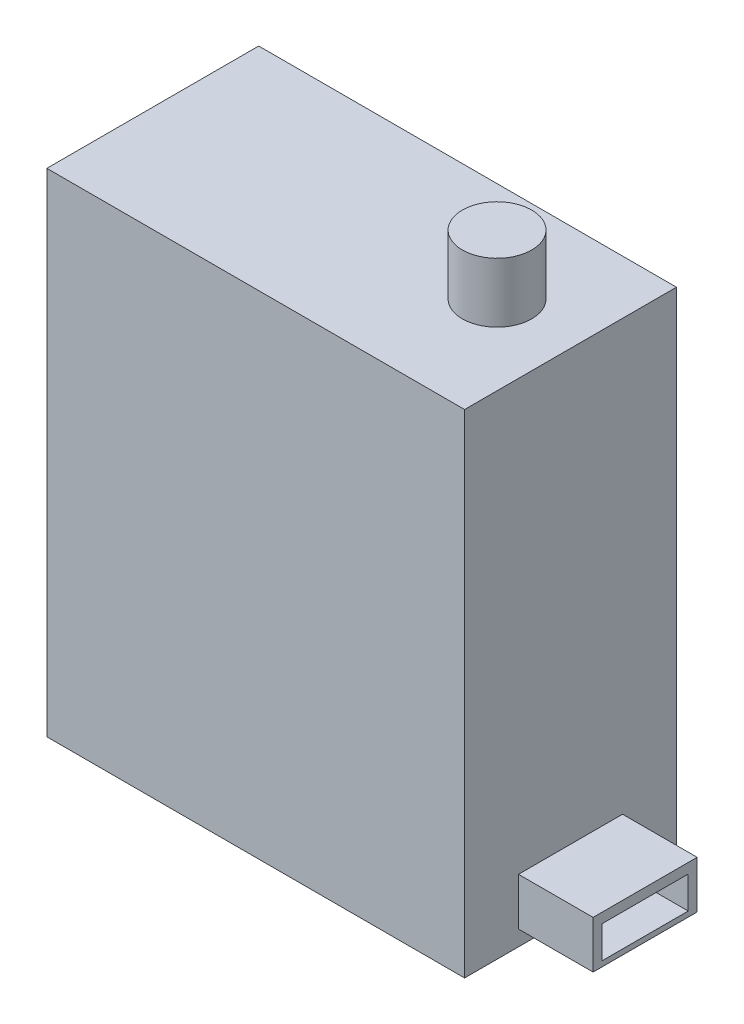
SolidWorks part; units mm, degrees
ref_plane "Front Plane" through (0, 0, 0) normal (0, 0, 1) x (1, 0, 0)
ref_plane "Top Plane" through (0, 0, 0) normal (0, 1, 0) x (1, 0, 0)
ref_plane "Right Plane" through (0, 0, 0) normal (1, 0, 0) x (0, 0, -1)
sketch "Sketch1" plane through (0, 0, 0) normal (0, 1, 0) x (1, 0, 0)
  line L1 (0, 0) -> (-28, 0)
  line L2 (0, 0) -> (0, 14.2)
  line L3 (0, 14.2) -> (-28, 14.2)
  line L4 (-28, 0) -> (-28, 14.2)
  dimension "D1" = 28
  dimension "D2" = 14.2
extrude "Boss-Extrude1" add sketch "Sketch1" along normal blind 33
sketch "Sketch2" plane through (0, 33, 0) normal (0, 1, 0) x (1, 0, 0)
  circle A0 centre (-5.3315, 7.5063) radius 2.3219
  dimension "D1" = 4.6438
extrude "Boss-Extrude3" add sketch "Sketch2" along normal blind 4
sketch "Sketch3" plane through (0, 0, 0) normal (1, 0, 0) x (0, 0, -1)
  line L1 (10.5874, 1.0363) -> (3.6126, 1.0363)
  line L2 (10.5874, 1.0363) -> (10.5874, 4.2126)
  line L3 (10.5874, 4.2126) -> (3.6126, 4.2126)
  line L4 (3.6126, 1.0363) -> (3.6126, 4.2126)
  line L5 (10.5874, 1.0363) -> (3.6126, 4.2126) construction
  line L6 (10.5874, 4.2126) -> (3.6126, 1.0363) construction
  point P0 (7.1, 2.6245)
  dimension "D1" = 24.485
  dimension "D2" = 6.9748
  dimension "D3" = 3.1763
  dimension "D4" = 6.9748
extrude "Boss-Extrude4" add sketch "Sketch3" along normal blind 5
sketch "Sketch4" plane through (5, 0, 0) normal (1, 0, 0) x (0, 0, -1)
  line L5 (4.2112, 1.393) -> (9.9888, 1.393)
  line L6 (4.2112, 1.393) -> (4.2112, 3.5428)
  line L7 (4.2112, 3.5428) -> (9.9888, 3.5428)
  line L8 (9.9888, 1.393) -> (9.9888, 3.5428)
  line L9 (4.2112, 1.393) -> (9.9888, 3.5428) construction
  line L10 (4.2112, 3.5428) -> (9.9888, 1.393) construction
  point P0 (7.1, 2.4679)
extrude "Cut-Extrude1" cut sketch "Sketch4" against normal blind 5
ref_plane "Plane1" through (-28, 0, 0) normal (0, -1, 0) x (-1, 0, 0)
sketch "Sketch6" plane through (-28, 0, 0) normal (-1, 0, 0) x (0, 0, 1)
  line L0 (0, 0) -> (0, 22)
  line L1 (0, 33) -> (0, 0) construction
  line L2 (0, 22) -> (-14.2, 22)
  line L3 (-14.2, 33) -> (-14.2, 0) construction
